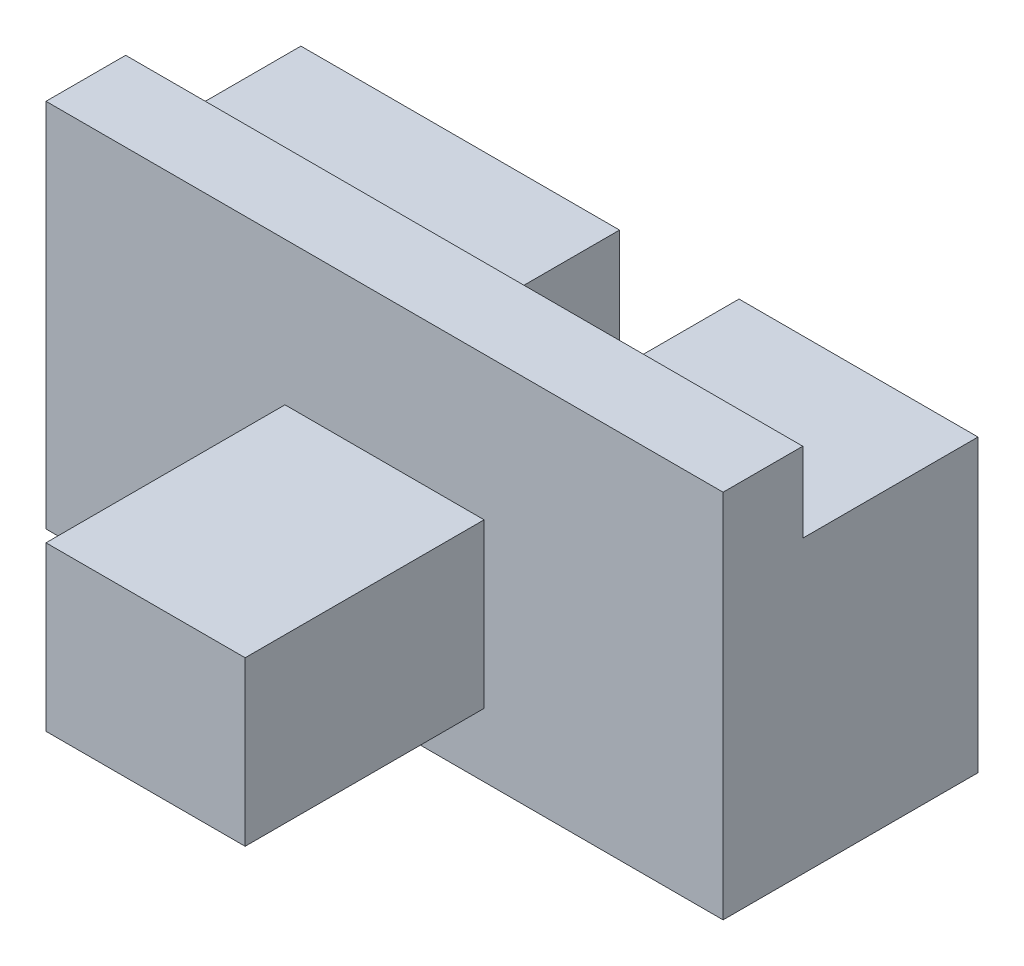
SolidWorks part; units mm, degrees
ref_plane "Front" through (0, 0, 0) normal (0, 0, 1) x (1, 0, 0)
ref_plane "Top" through (0, 0, 0) normal (0, 1, 0) x (1, 0, 0)
ref_plane "Right" through (0, 0, 0) normal (1, 0, 0) x (0, 0, -1)
sketch "Sketch1" plane through (0, 0, 0) normal (0, 0, 1) x (1, 0, 0)
  line L0 (-4.25, -1.825) -> (-4.25, 1.825)
  line L1 (-4.25, -1.825) -> (4.25, -1.825)
  line L3 (-4.25, 1.825) -> (4.25, 1.825)
  line L4 (4.25, -1.825) -> (4.25, 1.825)
  line L5 (4.25, 1.825) -> (-4.25, -1.825) construction
  point P0 (0, 1.825)
  point P5 (0, 0)
  dimension "D1" = 8.5
  dimension "D2" = 3.65
extrude "Boss-Extrude1" add sketch "Sketch1" along normal blind 1
sketch "Sketch2" plane through (0, 0, 1) normal (0, 0, 1) x (1, 0, 0)
  line L0 (-4.25, 1.825) -> (-4.25, -1.825) construction
  line L1 (-1.25, -1.025) -> (1.25, -1.025)
  line L2 (-1.25, -1.025) -> (-1.25, 1.025)
  line L3 (-1.25, 1.025) -> (1.25, 1.025)
  line L4 (1.25, -1.025) -> (1.25, 1.025)
  line L8 (-4.25, 1.825) -> (4.25, 1.825) construction
  line L9 (-4.25, -1.825) -> (4.25, -1.825) construction
  dimension "D1" = 3
  dimension "D2" = 2.5
  dimension "D4" = 0.8
  dimension "D5" = 0.8
extrude "Boss-Extrude2" add sketch "Sketch2" along normal blind 3
sketch "Sketch3" plane through (0, 0, 0) normal (0, 0, -1) x (-1, 0, 0)
  line L0 (-4.25, 1.825) -> (4.25, 1.825) construction
  line L1 (4.25, -1.825) -> (0.25, -1.825)
  line L2 (4.25, -1.825) -> (4.25, 1.825)
  line L3 (4.25, 1.825) -> (0.25, 1.825)
  line L4 (0.25, -1.825) -> (0.25, 1.825)
  line L6 (-4.25, -1.825) -> (-1.25, -1.825)
  line L7 (-4.25, -1.825) -> (-4.25, 1.825)
  line L8 (-4.25, 1.825) -> (-1.25, 1.825)
  line L9 (-1.25, -1.825) -> (-1.25, 1.825)
  dimension "D1" = 4
  dimension "D2" = 1.5
extrude "Boss-Extrude3" add sketch "Sketch3" along normal blind 2.2
sketch "Sketch4" plane through (0, 1.825, 0) normal (0, 1, 0) x (1, 0, 0)
  line L0 (4.25, -1) -> (4.25, 2.2) construction
  line L1 (-4.25, -1) -> (4.25, -1)
  line L2 (-4.25, -1) -> (-4.25, 0)
  line L3 (-4.25, 0) -> (4.25, 0)
  line L4 (4.25, -1) -> (4.25, 0)
  line L5 (1.25, 0) -> (-0.25, 0) construction
  dimension "D1" = 1
extrude "Boss-Extrude4" add sketch "Sketch4" along normal blind 1
